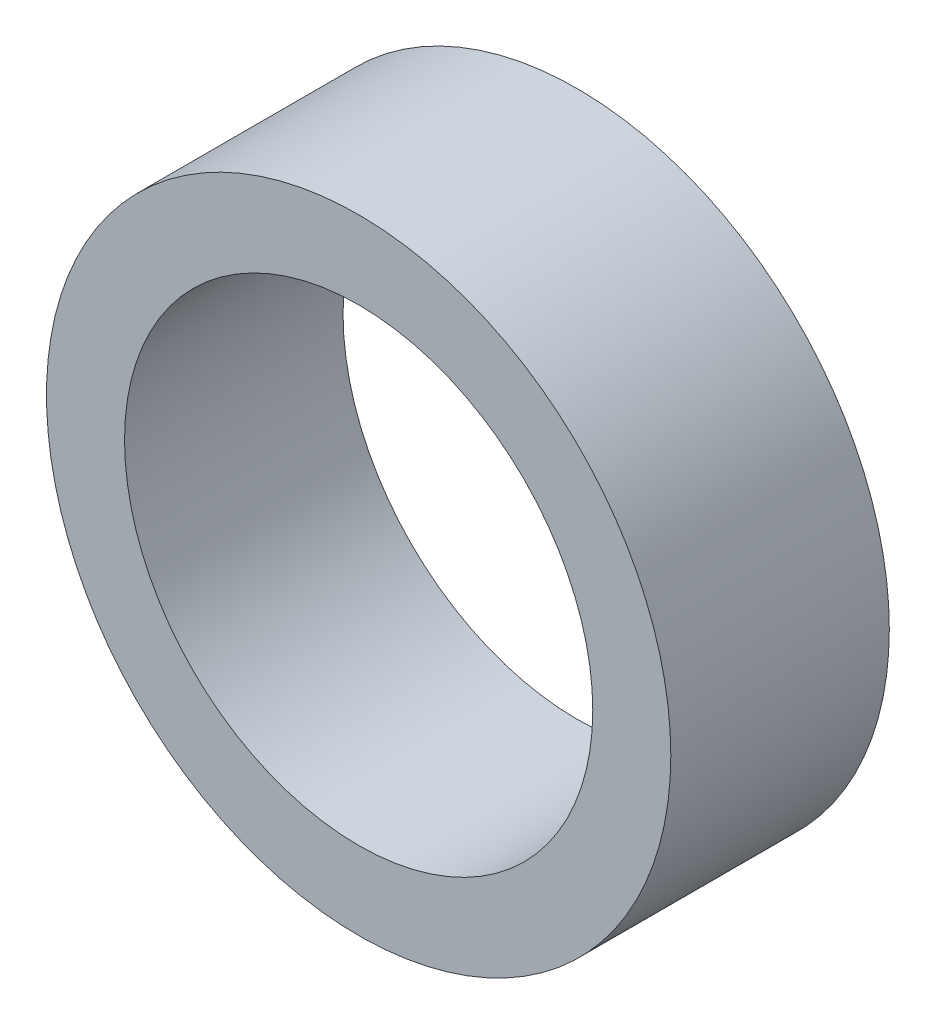
SolidWorks part; units mm, degrees
ref_plane "Front Plane" through (0, 0, 0) normal (0, 0, 1) x (1, 0, 0)
ref_plane "Top Plane" through (0, 0, 0) normal (0, 1, 0) x (1, 0, 0)
ref_plane "Right Plane" through (0, 0, 0) normal (1, 0, 0) x (0, 0, -1)
sketch "Sketch1" plane through (0, 0, 0) normal (0, 0, 1) x (1, 0, 0)
  circle A0 centre (-20, -10) radius 3
  circle A1 centre (-20, -10) radius 4
extrude "Boss-Extrude1" add sketch "Sketch1" along normal blind 2.8
